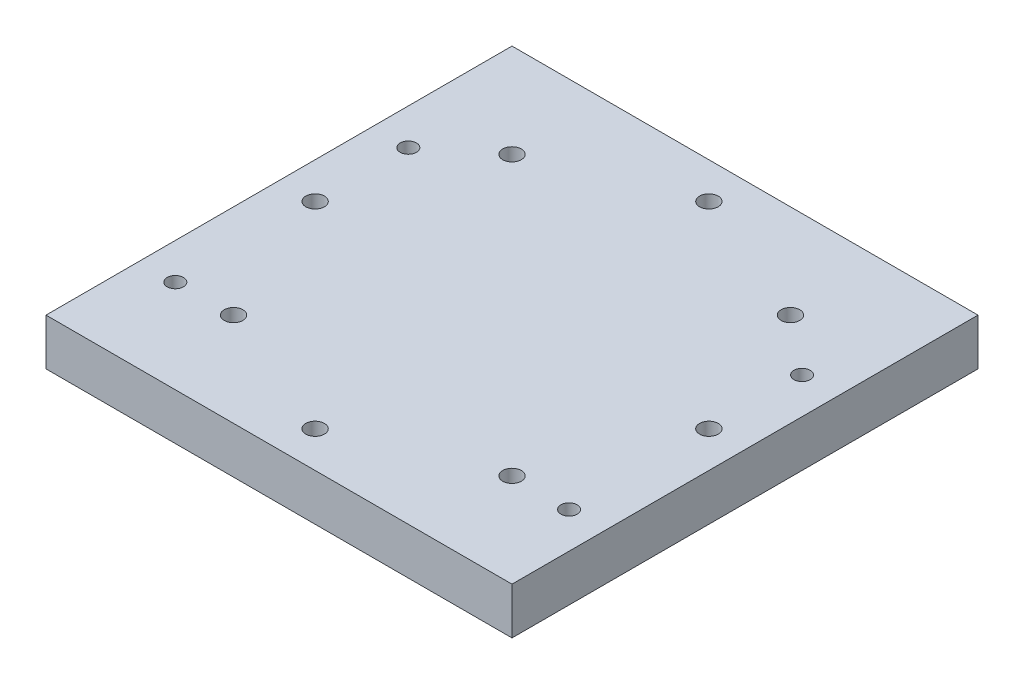
SolidWorks part; units mm, degrees
ref_plane "Front Plane" through (0, 0, 0) normal (0, 0, 1) x (1, 0, 0)
ref_plane "Top Plane" through (0, 0, 0) normal (0, 1, 0) x (1, 0, 0)
ref_plane "Right Plane" through (0, 0, 0) normal (1, 0, 0) x (0, 0, -1)
sketch "Sketch2" plane through (0, 0, 0) normal (0, 1, 0) x (1, 0, 0)
  line L0 (0, 0) -> (100, 100) construction
  line L1 (0, 0) -> (100, 0)
  line L2 (0, 0) -> (0, 100)
  line L3 (0, 100) -> (100, 100)
  line L4 (100, 0) -> (100, 100)
  line L5 (7.75, 95) -> (7.75, 5) construction
  line L6 (7.75, 50) -> (50, 50) construction
  line L7 (50, 50) -> (50, 92.25) construction
  line L8 (7.75, 70) -> (7.75, 20) construction
  circle A0 centre (50, 50) radius 45 construction
  circle A1 centre (50, 50) radius 39.5 construction
  circle A2 centre (50, 50) radius 42.25 construction
  circle A3 centre (50, 92.25) radius 2
  circle A4 centre (79.8753, 79.8753) radius 2
  circle A5 centre (92.25, 50) radius 2
  circle A6 centre (79.8753, 20.1247) radius 2
  circle A7 centre (50, 7.75) radius 2
  circle A8 centre (20.1247, 20.1247) radius 2
  circle A9 centre (7.75, 50) radius 2
  circle A10 centre (20.1247, 79.8753) radius 2
  circle A11 centre (7.75, 20) radius 1.75
  circle A12 centre (7.75, 70) radius 1.75
  circle A13 centre (92.25, 20) radius 1.75
  circle A14 centre (92.25, 70) radius 1.75
  point P27 (50, 50)
  point P36 (7.75, 75)
  point P37 (0, 0)
  point P38 (7.75, 25)
  point P39 (0, 0)
  point P40 (0, 0)
  point P41 (0, 0)
  dimension "D1" = 90
  dimension "D2" = 50
  dimension "D4" = 5.5
  dimension "D5" = 2.75
  dimension "D6" = 4
  dimension "D9" = 50
  dimension "D10" = 3.5
  dimension "D3" = 50
  dimension "D8" = 90
  dimension "D11" = 20
  dimension "D7" = 8
extrude "Boss-Extrude1" add sketch "Sketch2" along normal blind 10
